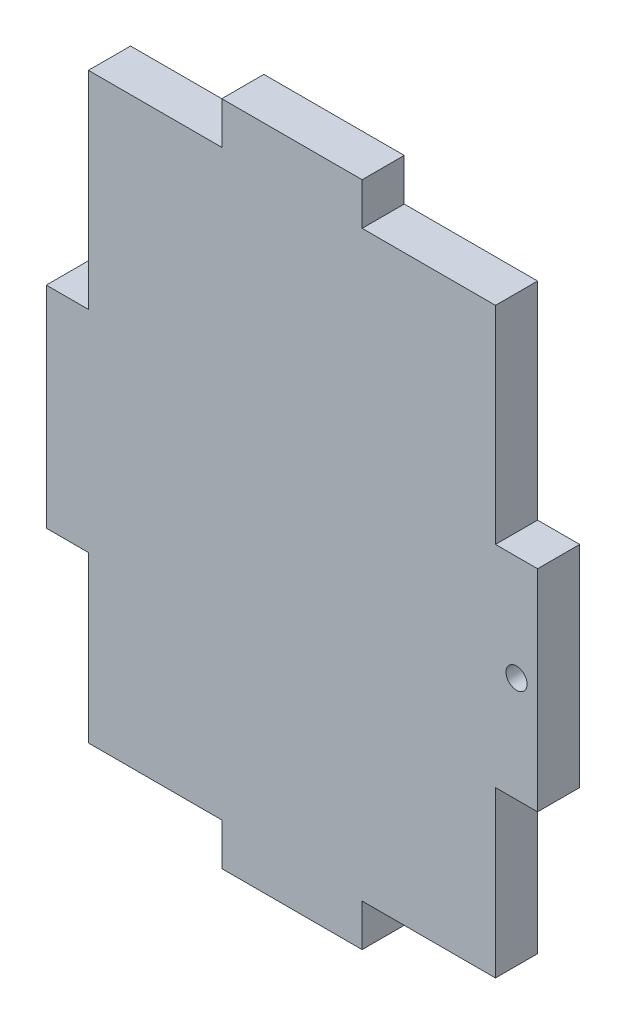
SolidWorks part; units mm, degrees
ref_plane "Plan de face" through (0, 0, 0) normal (0, 0, 1) x (1, 0, 0)
ref_plane "Plan de dessus" through (0, 0, 0) normal (0, 1, 0) x (1, 0, 0)
ref_plane "Plan de droite" through (0, 0, 0) normal (1, 0, 0) x (0, 0, -1)
sketch "Esquisse1" plane through (0, 0, 0) normal (0, 0, 1) x (1, 0, 0)
  line L1 (0, 0) -> (-70, 0)
  line L2 (0, 0) -> (0, 95)
  line L3 (0, 95) -> (-70, 95)
  line L4 (-70, 0) -> (-70, 95)
  dimension "D1" = 95
  dimension "D2" = 70
extrude "Boss.-Extru.1" add sketch "Esquisse1" along normal blind 6
sketch "Esquisse2" plane through (0, 0, 0) normal (0, 0, -1) x (-1, 0, 0)
  line L0 (0, 95) -> (70, 95) construction
  line L1 (0, 95) -> (25, 95)
  line L2 (0, 95) -> (0, 59.5)
  line L3 (6, 89) -> (25, 89)
  line L4 (25, 95) -> (25, 89)
  line L5 (70, 95) -> (45, 95)
  line L6 (0, 0) -> (25, 0)
  line L7 (64, 89) -> (45, 89)
  line L8 (45, 95) -> (45, 89)
  line L9 (70, 95) -> (70, 0) construction
  line L10 (45, 0) -> (70, 0)
  line L11 (70, 95) -> (70, 59.5)
  line L12 (70, 0) -> (70, 29.5)
  line L13 (0, 59.5) -> (6, 59.5)
  line L14 (6, 89) -> (6, 59.5)
  line L16 (0, 0) -> (0, 29.5)
  line L17 (0, 29.5) -> (6, 29.5)
  line L18 (6, 6) -> (6, 29.5)
  line L21 (6, 6) -> (25, 6)
  line L22 (25, 0) -> (25, 6)
  line L25 (64, 6) -> (45, 6)
  line L26 (45, 0) -> (45, 6)
  line L29 (70, 29.5) -> (64, 29.5)
  line L30 (64, 6) -> (64, 29.5)
  line L33 (70, 59.5) -> (64, 59.5)
  line L34 (64, 89) -> (64, 59.5)
  dimension "D1" = 6
  dimension "D2" = 20
  dimension "D3" = 6
  dimension "D4" = 25
  dimension "D5" = 6
  dimension "D6" = 30
  dimension "D7" = 35.5
  dimension "D8" = 6
  dimension "D9" = 6
  dimension "D10" = 6
  dimension "D11" = 29.5
  dimension "D12" = 19
  dimension "D13" = 20
  dimension "D14" = 6
  dimension "D15" = 30
  dimension "D16" = 6
extrude "Enlèv. mat.-Extru.1" cut sketch "Esquisse2" against normal through all
sketch "Esquisse3" plane through (0, 0, 0) normal (0, 0, -1) x (-1, 0, 0)
  line L0 (0, 29.5) -> (0, 59.5) construction
  line L1 (0, 59.5) -> (6, 59.5) construction
  circle A0 centre (3, 44.5) radius 1.5
  dimension "D1" = 3
  dimension "D2" = 3
  dimension "D3" = 15
extrude "Enlèv. mat.-Extru.2" cut sketch "Esquisse3" against normal through all
sketch "Esquisse4" plane through (0, 0, 0) normal (0, 0, -1) x (-1, 0, 0)
  circle A0 centre (3, 44.5) radius 2.995
  dimension "D1" = 5.99
extrude "Enlèv. mat.-Extru.3" cut sketch "Esquisse4" against normal blind 3
